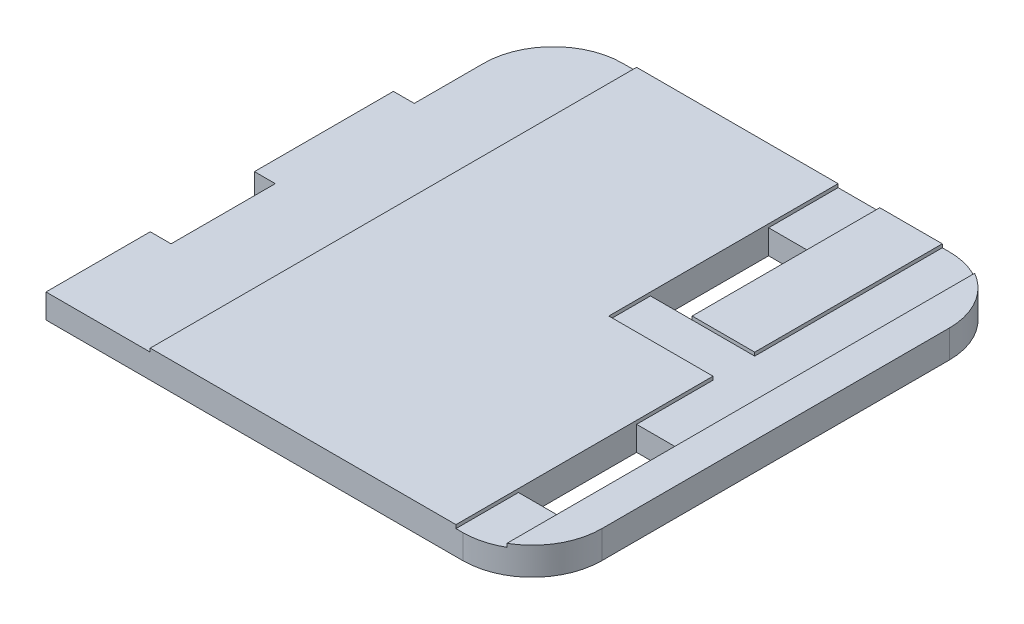
SolidWorks part; units mm, degrees
material "PBT General Purpose"
ref_plane "Front Plane" through (0, 0, 0) normal (0, 0, 1) x (1, 0, 0)
ref_plane "Top Plane" through (0, 0, 0) normal (0, 1, 0) x (1, 0, 0)
ref_plane "Right Plane" through (0, 0, 0) normal (1, 0, 0) x (0, 0, -1)
sketch "Sketch1" plane through (0, 0, 0) normal (0, 1, 0) x (1, 0, 0)
  line L0 (0, 0) -> (7, 0)
  line L5 (7, 0) -> (7, 7)
  line L6 (7, 7) -> (0.3, 7)
  line L7 (0.3, 7) -> (0.3, 5)
  line L8 (0.3, 5) -> (0, 5)
  line L9 (0, 5) -> (0, 3)
  line L10 (0, 3) -> (0.3, 3)
  line L11 (0.3, 3) -> (0.3, 1.5)
  line L12 (0.3, 1.5) -> (0, 1.5)
  line L13 (0, 1.5) -> (0, 0)
  line L15 (4.4, 6) -> (5, 6)
  line L16 (4.4, 6) -> (4.4, 4.3)
  line L17 (4.4, 4.3) -> (5, 4.3)
  line L18 (5, 6) -> (5, 4.3)
  line L19 (5.9, 0.9) -> (6.5, 0.9)
  line L20 (5.9, 0.9) -> (5.9, 2.6)
  line L21 (5.9, 2.6) -> (6.5, 2.6)
  line L22 (6.5, 0.9) -> (6.5, 2.6)
  dimension "D1" = 2
  dimension "D2" = 1.5
  dimension "D3" = 1.5
  dimension "D4" = 2
  dimension "D5" = 5.6
  dimension "D7" = 1.7
  dimension "D8" = 0.6
  dimension "D9" = 0.3
  dimension "D10" = 4.1
  dimension "D11" = 0.6
  dimension "D12" = 1.7
  dimension "D13" = 1
  dimension "D14" = 7
  dimension "D6" = 4.4
extrude "Boss-Extrude1" add sketch "Sketch1" along normal blind 0.4
fillet "Fillet1" radius 1 3 edges at (7, 0.2, 0) (7, 0.2, -7) (0.3, 0.2, -7)
sketch "Sketch3" plane through (0, 0.4, 0) normal (0, 1, 0) x (1, 0, 0)
  line L0 (6, 7) -> (1.3, 7) construction
  line L1 (4.4, 6) -> (5, 6)
  line L2 (4.4, 6) -> (4.4, 7)
  line L3 (4.4, 7) -> (5, 7)
  line L4 (5, 6) -> (5, 7)
  line L5 (0, 0) -> (6, 0) construction
  line L6 (5.9, 0.9) -> (6.5, 0.9)
  line L7 (5.9, 0.9) -> (5.9, 0)
  line L8 (5.9, 0) -> (6.5, 0)
  line L9 (6.5, 0.9) -> (6.5, 0)
  line L10 (6.5, 0.9) -> (6.5, 2.6) construction
  line L11 (5, 4.3) -> (5, 6) construction
  line L12 (4.4, 4.3) -> (4.4, 3.7)
  line L14 (6.5, 2.6) -> (5.9, 2.6)
  line L15 (4.4, 4.3) -> (5, 4.3)
  line L16 (5.9, 3.7) -> (5.9, 2.6)
  line L17 (6.5, 2.6) -> (6.5, 3.7)
  line L18 (0, 0) -> (1.5, 0)
  line L19 (0, 0) -> (0, 7)
  line L20 (0, 7) -> (1.5, 7)
  line L21 (1.5, 0) -> (1.5, 7)
  line L22 (4.4, 3.7) -> (5.9, 3.7)
  line L24 (5, 4.3) -> (5.9, 4.3)
  line L26 (5.9, 4.3) -> (5.9, 7)
  line L27 (6.5, 3.7) -> (6.5, 4.3)
  line L28 (6.5, 4.3) -> (6.5, 7)
  line L29 (6.5, 7) -> (6.5, 7.2689)
  line L30 (6.5, 7.2689) -> (5.9, 7.2689)
  line L31 (5.9, 7.2689) -> (5.9, 7)
  line M15 (0, 0) -> (6, 0)
  line M19 (6, 7) -> (1.3, 7)
  arc M20 (1.3, 7) -> (0.3, 6) centre (1.3, 6) ccw
  line M21 (0.3, 6) -> (0.3, 5)
  line M22 (0.3, 5) -> (0, 5)
  line M23 (0, 5) -> (0, 3)
  line M24 (0, 3) -> (0.3, 3)
  line M25 (0.3, 3) -> (0.3, 1.5)
  line M26 (0.3, 1.5) -> (0, 1.5)
  line M27 (0, 1.5) -> (0, 0)
  dimension "D1" = 1.5
extrude "Cut-Extrude2" cut sketch "Sketch3" against normal blind 0.05 contours L21 M15 M19 M20 M21 M22 M23 M24 M25 M26 M27 | L7 L6 L9 L8 | L15 L24 L26 L31 L30 L29 L28 L27 L17 L14 L16 L22 L12 | L2 L1 L4 L3
equation "\"t\"= 0.3'thickness of the sheets"
equation "\"FlexJoint\"= 0.15'Width of flextures"
equation "\"FoldJoint\"= 0.4'Width of folding joints"
equation "\"AssembleAngle\"= 90'Angle of assembly parts"
equation "\"D9@Sketch1\"=\"t\""
